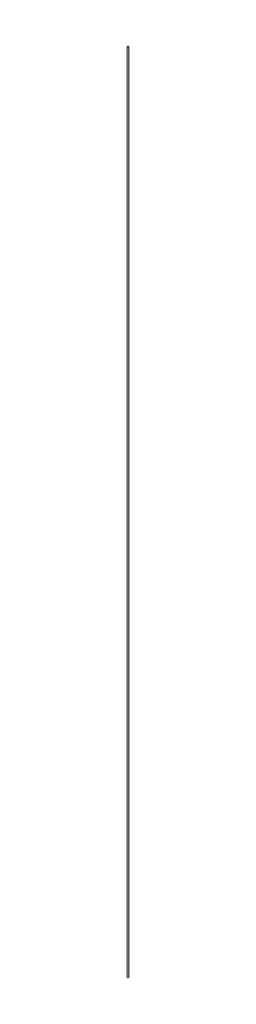
SolidWorks part; units mm, degrees
ref_plane "Front Plane" through (0, 0, 0) normal (0, 0, 1) x (1, 0, 0)
ref_plane "Top Plane" through (0, 0, 0) normal (0, 1, 0) x (1, 0, 0)
ref_plane "Right Plane" through (0, 0, 0) normal (1, 0, 0) x (0, 0, -1)
sketch "Sketch1" plane through (0, 0, 0) normal (0, 0, 1) x (1, 0, 0)
  line L0 (0, 0) -> (0, 8812.784)
  dimension "D1" = 8812.784
sweep "Sweep1" add path "Sketch1" circular profile diameter 12.7 parameters "D3"=12.7
